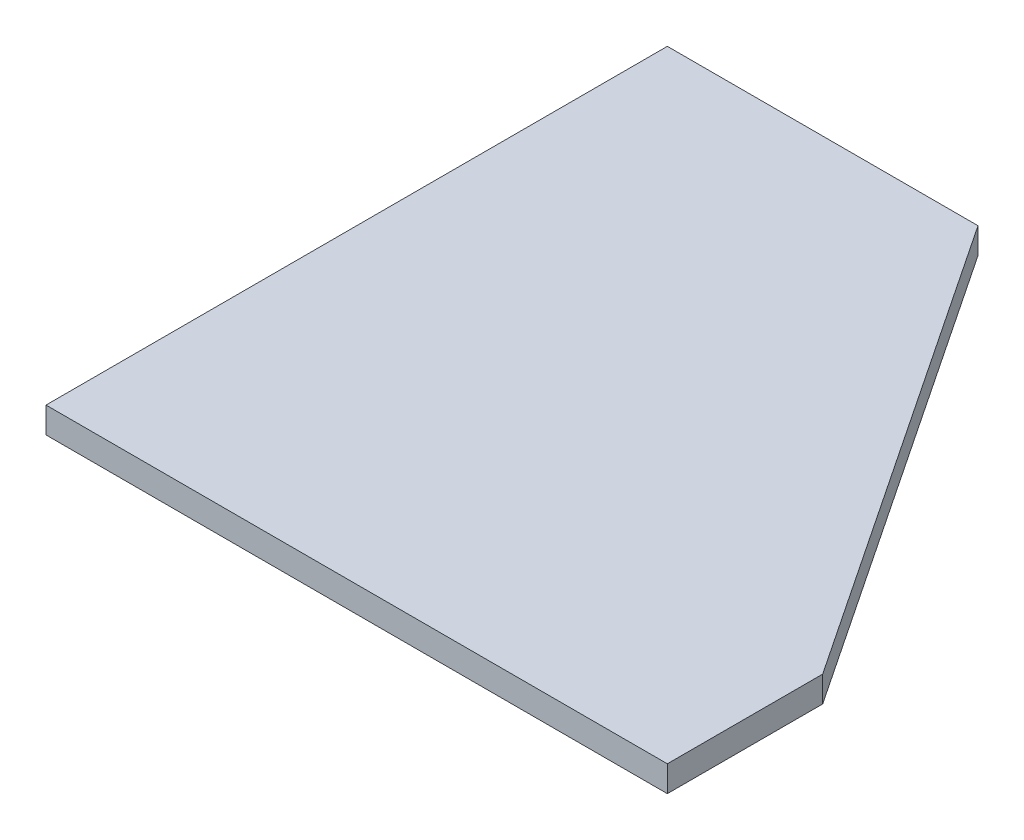
SolidWorks part; units mm, degrees
ref_plane "Front Plane" through (0, 0, 0) normal (0, 0, 1) x (1, 0, 0)
ref_plane "Top Plane" through (0, 0, 0) normal (0, 1, 0) x (1, 0, 0)
ref_plane "Right Plane" through (0, 0, 0) normal (1, 0, 0) x (0, 0, -1)
sketch "Sketch1" plane through (0, 0, 0) normal (0, 1, 0) x (1, 0, 0)
  line L0 (0, 0) -> (0, 152.4)
  line L1 (0, 152.4) -> (76.2, 152.4)
  line L2 (76.2, 152.4) -> (152.4, 38.1)
  line L3 (152.4, 38.1) -> (152.4, 0)
  line L4 (152.4, 0) -> (0, 0)
  line L5 (19.05, 152.4) -> (19.05, 0) construction
  line L6 (152.4, 19.05) -> (0, 19.05) construction
  line L7 (57.15, 152.4) -> (57.15, 0) construction
  point P10 (19.05, 133.35)
  point P11 (19.05, 95.25)
  point P12 (19.05, 57.15)
  point P13 (19.05, 19.05)
  point P14 (57.15, 19.05)
  point P15 (95.25, 19.05)
  point P16 (133.35, 19.05)
  point P33 (57.15, 133.35)
  point P34 (57.15, 95.25)
  point P35 (57.15, 57.15)
  dimension "D1" = 152.4
  dimension "D2" = 152.4
  dimension "D3" = 38.1
  dimension "D4" = 76.2
  dimension "D5" = 38.1
  dimension "D6" = 38.1
  dimension "D7" = 38.1
  dimension "D8" = 38.1
  dimension "D9" = 38.1
  dimension "D10" = 38.1
  dimension "D13" = 38.1
  dimension "D14" = 38.1
  dimension "D15" = 38.1
  dimension "D16" = 38.1
extrude "Extrude1" add sketch "Sketch1" along normal blind 6.35
